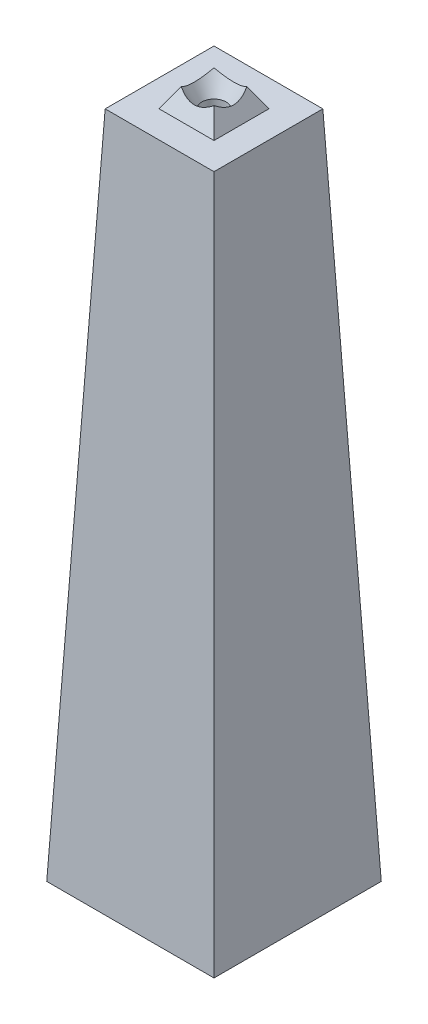
SolidWorks part; units mm, degrees
ref_plane "Front Plane" through (0, 0, 0) normal (0, 0, 1) x (1, 0, 0)
ref_plane "Top Plane" through (0, 0, 0) normal (0, 1, 0) x (1, 0, 0)
ref_plane "Right Plane" through (0, 0, 0) normal (1, 0, 0) x (0, 0, -1)
sketch "Sketch1" plane through (0, 0, 0) normal (0, 1, 0) x (1, 0, 0)
  line L1 (0, 0) -> (47.625, 0)
  line L2 (0, 0) -> (0, -47.625)
  line L3 (0, -47.625) -> (47.625, -47.625)
  line L4 (47.625, 0) -> (47.625, -47.625)
  dimension "D1" = 47.625
  dimension "D2" = 47.625
  dimension "D3" = 0
  dimension "D4" = 0
extrude "Boss-Extrude1" add sketch "Sketch1" along normal blind 381 draft 2.5
sketch "Sketch2" plane through (0, 0, 0) normal (0, -1, 0) x (1, 0, 0)
  line L0 (0, 23.8125) -> (47.625, 23.8125) construction
  line L1 (0, 0) -> (0, 47.625) construction
  line L2 (47.625, 47.625) -> (47.625, 0) construction
  line L3 (23.8125, 47.625) -> (23.8125, 0) construction
  line L4 (0, 47.625) -> (47.625, 47.625) construction
  line L5 (47.625, 0) -> (0, 0) construction
  circle A0 centre (23.8125, 23.8125) radius 3.429
  dimension "D1" = 6.858
extrude "Cut-Extrude1" cut sketch "Sketch2" against normal blind 381
sketch "Sketch3" plane through (0, 0, 0) normal (0, -1, 0) x (1, 0, 0)
  line L1 (0, 47.625) -> (47.625, 47.625)
  line L2 (0, 47.625) -> (0, 0)
  line L3 (0, 0) -> (47.625, 0)
  line L4 (47.625, 47.625) -> (47.625, 0)
sketch "Sketch5" plane through (0, 381, 0) normal (0, 1, 0) x (1, 0, 0)
  line L1 (0, 0) -> (47.625, 0)
  line L2 (0, 0) -> (0, -47.625)
  line L3 (0, -47.625) -> (47.625, -47.625)
  line L4 (47.625, 0) -> (47.625, -47.625)
extrude "Cut-Extrude4" cut sketch "Sketch5" against normal blind 190.5
sketch "Sketch6" plane through (0, 190.5, 0) normal (0, 1, 0) x (1, 0, 0)
  line L0 (39.3076, -23.8125) -> (8.3174, -23.8125) construction
  line L1 (39.3076, -39.3076) -> (39.3076, -8.3174) construction
  line L2 (8.3174, -8.3174) -> (8.3174, -39.3076) construction
  line L3 (23.8125, -8.3174) -> (23.8125, -39.3076) construction
  line L4 (39.3076, -8.3174) -> (8.3174, -8.3174) construction
  line L5 (8.3174, -39.3076) -> (39.3076, -39.3076) construction
  line L7 (16.002, -16.002) -> (31.623, -16.002)
  line L8 (16.002, -16.002) -> (16.002, -31.623)
  line L9 (16.002, -31.623) -> (31.623, -31.623)
  line L10 (31.623, -16.002) -> (31.623, -31.623)
  circle A0 centre (23.8125, -23.8125) radius 3.429
  dimension "D1" = 15.621
  dimension "D2" = 15.621
  dimension "D3" = 7.8105
  dimension "D4" = 7.8105
extrude "Boss-Extrude2" add sketch "Sketch6" along normal blind 6.35 draft 30
